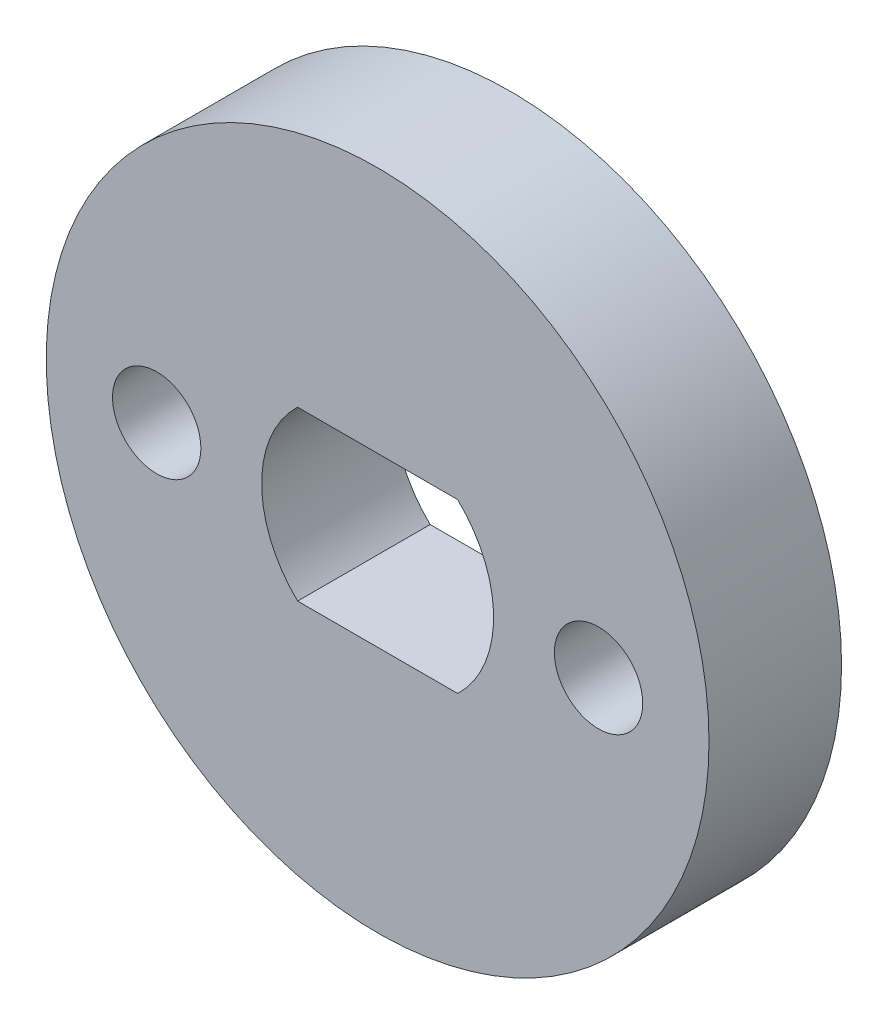
SolidWorks part; units mm, degrees
ref_plane "Front Plane" through (0, 0, 0) normal (0, 0, 1) x (1, 0, 0)
ref_plane "Top Plane" through (0, 0, 0) normal (0, 1, 0) x (1, 0, 0)
ref_plane "Right Plane" through (0, 0, 0) normal (1, 0, 0) x (0, 0, -1)
sketch "Sketch1" plane through (0, 0, 0) normal (0, 0, 1) x (1, 0, 0)
  circle A0 centre (0, 0) radius 7.5
extrude "Boss-Extrude1" add sketch "Sketch1" along normal blind 3
sketch "Sketch5" plane through (0, 0, 3) normal (0, 0, 1) x (1, 0, 0)
  line L0 (-1.8112, 1.9) -> (-1.8112, -1.9)
  arc A0 (-1.8112, 1.9) -> (-1.8112, -1.9) centre (0, 0) ccw
  dimension "D1" = 3.8
  dimension "D2" = 2.625
sketch "Sketch6" plane through (0, 0, 3) normal (0, 0, 1) x (1, 0, 0)
  line L1 (-1.8112, 1.9) -> (0, 1.9)
  line L2 (-1.8112, 1.9) -> (-1.8112, -1.9)
  line L3 (-1.8112, -1.9) -> (0, -1.9)
  line L4 (0, 1.9) -> (0, -1.9)
extrude "Cut-Extrude1" cut sketch "Sketch5" against normal blind 3
extrude "Cut-Extrude2" cut sketch "Sketch6" against normal blind 3
mirror "Mirror1" about plane through (0, 0, 0) normal (1, 0, 0) of "Cut-Extrude2", "Cut-Extrude1"
hole_wizard "Ø2.0mm Dowel Hole1" positions "Sketch8" profile "Sketch9" hole size "Ø2.0" standard "ANSI Metric"
sketch "Sketch8" plane through (0, 0, 3) normal (0, 0, 1) x (1, 0, 0)
  point P0 (5, 0)
  point P2 (-5, 0)
  dimension "D1" = 5
  dimension "D2" = 5
sketch "Sketch9" plane through (5, 0, 3) normal (1, 0, 0) x (0, -1, 0)
  line L0 (0, 0) -> (0, 3.5999)
  line L1 (0, 3.5999) -> (1, 2.999)
  line L2 (1, 2.999) -> (1, 0)
  line L5 (1, 0) -> (0, 0)
  line L10 (0, 3.5999) -> (-1, 2.999) construction
  line L11 (0, -6.35) -> (0, 107.95) construction
  dimension "Hole Dia." = 2
  dimension "Hole Depth" = 2.999
  dimension "Drill Angle" = 118
